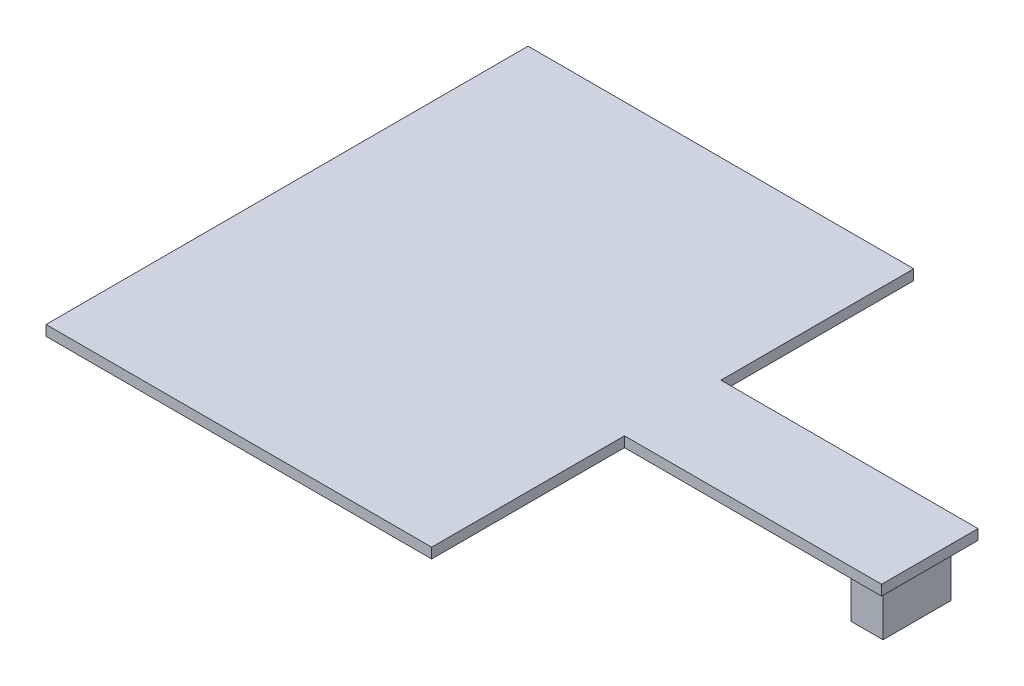
SolidWorks part; units mm, degrees
ref_plane "Front Plane" through (0, 0, 0) normal (0, 0, 1) x (1, 0, 0)
ref_plane "Top Plane" through (0, 0, 0) normal (0, 1, 0) x (1, 0, 0)
ref_plane "Right Plane" through (0, 0, 0) normal (1, 0, 0) x (0, 0, -1)
sketch "Sketch1" plane through (0, 0, 0) normal (0, 1, 0) x (1, 0, 0)
  line L0 (-55, 0) -> (55, 0) construction
  line L1 (-30, -37.5) -> (30, -37.5)
  line L2 (-30, -37.5) -> (-30, 37.5)
  line L3 (-30, 37.5) -> (30, 37.5)
  line L4 (30, -37.5) -> (30, 37.5)
  line L5 (-30, -37.5) -> (30, 37.5) construction
  line L6 (-30, 37.5) -> (30, -37.5) construction
  line L7 (70, -7.5) -> (30, -7.5)
  line L8 (70, -7.5) -> (70, 7.5)
  line L9 (70, 7.5) -> (30, 7.5)
  line L10 (30, -7.5) -> (30, 7.5)
  line L11 (70, -7.5) -> (30, 7.5) construction
  line L12 (70, 7.5) -> (30, -7.5) construction
  point P0 (0, 0)
  point P5 (50, 0)
  dimension "D1" = 60
  dimension "D2" = 75
  dimension "D3" = 15
  dimension "D4" = 40
extrude "Boss-Extrude1" add sketch "Sketch1" against normal blind 1.6 contours L1 L4 L3 L2 | L8 L9 L4 L7
sketch "Sketch2" plane through (0, -1.6, 0) normal (0, -1, 0) x (1, 0, 0)
  line L0 (0.88, 0) -> (-0.88, 0) construction
  line L1 (63, -5.28) -> (68, -5.28)
  line L2 (63, -5.28) -> (63, 5.28)
  line L3 (63, 5.28) -> (68, 5.28)
  line L4 (68, -5.28) -> (68, 5.28)
  line L5 (63, -5.28) -> (68, 5.28) construction
  line L6 (63, 5.28) -> (68, -5.28) construction
  line L7 (70, 7.5) -> (70, -7.5) construction
  point P0 (65.5, 0)
  dimension "D1" = 10.56
  dimension "D2" = 5
  dimension "D3" = 2
extrude "Boss-Extrude2" add sketch "Sketch2" along normal blind 8
